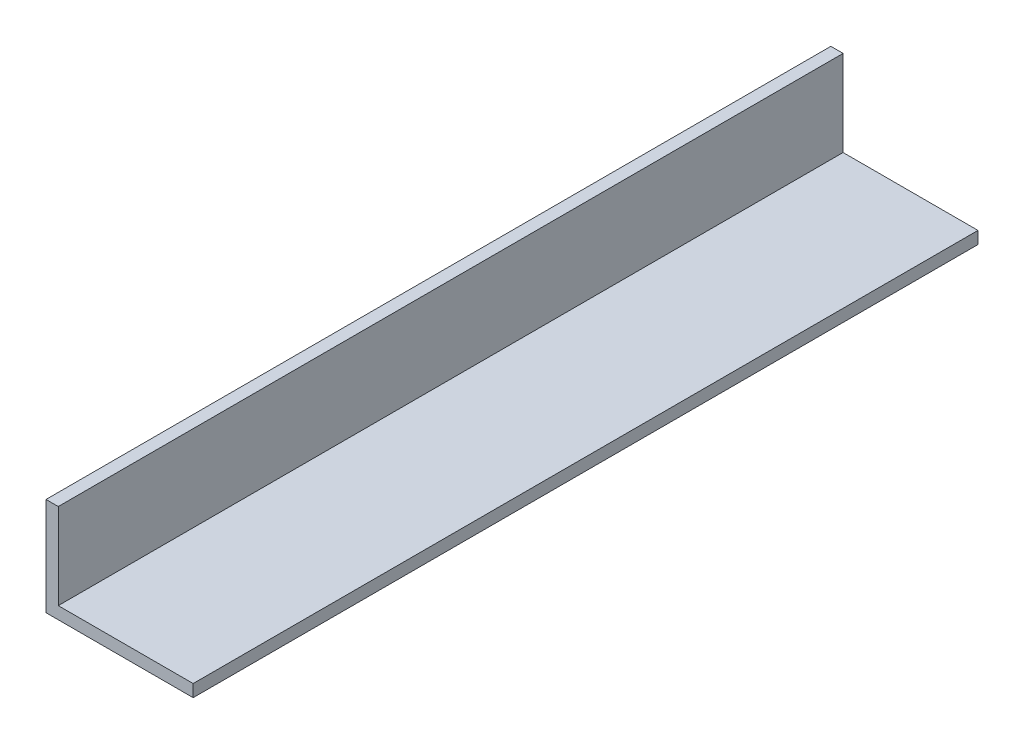
SolidWorks part; units mm, degrees
ref_plane "Front Plane" through (0, 0, 0) normal (0, 0, 1) x (1, 0, 0)
ref_plane "Top Plane" through (0, 0, 0) normal (0, 1, 0) x (1, 0, 0)
ref_plane "Right Plane" through (0, 0, 0) normal (1, 0, 0) x (0, 0, -1)
sketch "Sketch3" plane through (0, 0, 0) normal (0, 0, 1) x (1, 0, 0)
  line L0 (0, 0) -> (19.05, 0)
  line L1 (19.05, 0) -> (19.05, 1.5875)
  line L2 (19.05, 1.5875) -> (1.5875, 1.5875)
  line L3 (1.5875, 1.5875) -> (1.5875, 12.7)
  line L4 (1.5875, 12.7) -> (0, 12.7)
  line L5 (0, 12.7) -> (0, 0)
  dimension "D1" = 19.05
  dimension "D2" = 12.7
  dimension "D3" = 1.5875
  dimension "D4" = 1.5875
extrude "Boss-Extrude1" add sketch "Sketch3" along normal blind 101.6
sketch "Sketch4" plane through (1.5875, 0, 0) normal (1, 0, 0) x (0, 0, -1)
  line L0 (-101.6, 1.5875) -> (0, 1.5875) construction
  line L1 (-63.5, 1.5875) -> (-38.1, 1.5875)
  line L2 (-63.5, 1.5875) -> (-63.5, 5.3975)
  line L3 (-63.5, 5.3975) -> (-38.1, 5.3975)
  line L4 (-38.1, 1.5875) -> (-38.1, 5.3975)
  line L5 (-101.6, 12.7) -> (0, 12.7) construction
  point P8 (-50.8, 12.7)
  point P9 (-50.8, 5.3975)
  dimension "D1" = 25.4
  dimension "D2" = 3.81
extrude "Cut-Extrude1" [suppressed] cut sketch "Sketch4" against normal blind 2.54
